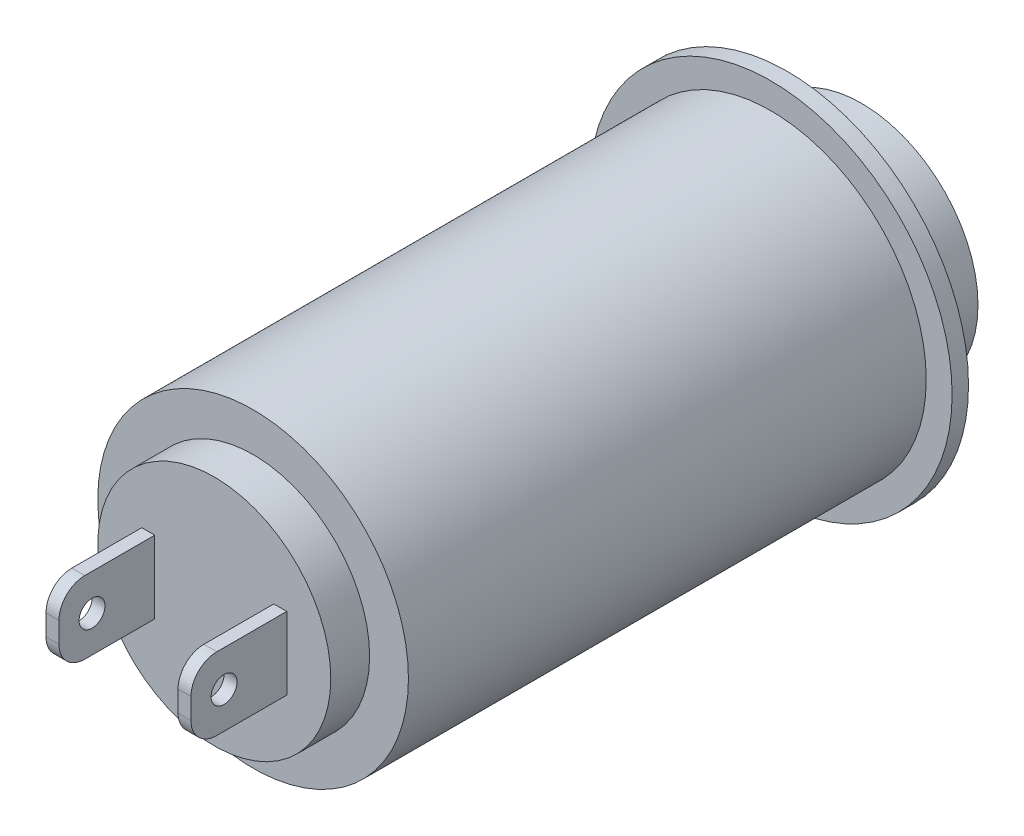
SolidWorks part; units mm, degrees
ref_plane "정면" through (0, 0, 0) normal (0, 0, 1) x (1, 0, 0)
ref_plane "윗면" through (0, 0, 0) normal (0, 1, 0) x (1, 0, 0)
ref_plane "우측면" through (0, 0, 0) normal (1, 0, 0) x (0, 0, -1)
sketch "스케치1" plane through (0, 0, 0) normal (0, 0, 1) x (1, 0, 0)
  circle A0 centre (0, 0) radius 4.5
  dimension "D1" = 9
extrude "보스-돌출1" add sketch "스케치1" along normal blind 2
sketch "스케치2" plane through (0, 0, 2) normal (0, 0, 1) x (1, 0, 0)
  circle A0 centre (0, 0) radius 7
extrude "보스-돌출2" add sketch "스케치2" along normal blind 1.5
sketch "스케치3" plane through (0, 0, 3.5) normal (0, 0, 1) x (1, 0, 0)
  circle A0 centre (0, 0) radius 6
extrude "보스-돌출3" add sketch "스케치3" along normal blind 20
sketch "스케치4" plane through (0, 0, 23.5) normal (0, 0, 1) x (1, 0, 0)
  circle A0 centre (0, 0) radius 4.5
extrude "보스-돌출4" add sketch "스케치4" along normal blind 1.5 contours A0
sketch "스케치5" plane through (0, 0, 25) normal (0, 0, 1) x (1, 0, 0)
  line L0 (0, 0) -> (-3.0732, 0) construction
  line L1 (0, 0) -> (0, 3.7176) construction
  line L2 (2.8, 1.4) -> (2.3, 1.4)
  line L3 (-2.8, -1.4) -> (-2.3, -1.4)
  line L4 (-2.8, -1.4) -> (-2.8, 1.4)
  line L5 (-2.8, 1.4) -> (-2.3, 1.4)
  line L6 (-2.3, -1.4) -> (-2.3, 1.4)
  line L7 (-2.8, -1.4) -> (-2.3, 1.4) construction
  line L8 (-2.8, 1.4) -> (-2.3, -1.4) construction
  line L9 (2.3, -1.4) -> (2.3, 1.4)
  line L10 (2.8, -1.4) -> (2.3, -1.4)
  line L11 (2.8, -1.4) -> (2.8, 1.4)
  point P3 (-2.55, 0)
  dimension "D1" = 0.5
  dimension "D2" = 2.8
  dimension "D3" = 2.55
extrude "보스-돌출5" add sketch "스케치5" along normal blind 3.7
chamfer "모따기1" distance 1.5 angle 30 1 edges at (7, 0, 2)
fillet "필렛1" radius 1 4 edges at (-2.55, -1.4, 28.7) (-2.55, 1.4, 28.7) (2.55, 1.4, 28.7) (2.55, -1.4, 28.7)
sketch "스케치6" plane through (-2.8, 0, 0) normal (-1, 0, 0) x (0, 0, 1)
  circle A0 centre (27.4218, 0) radius 0.5
extrude "컷-돌출1" cut sketch "스케치6" against normal through all
